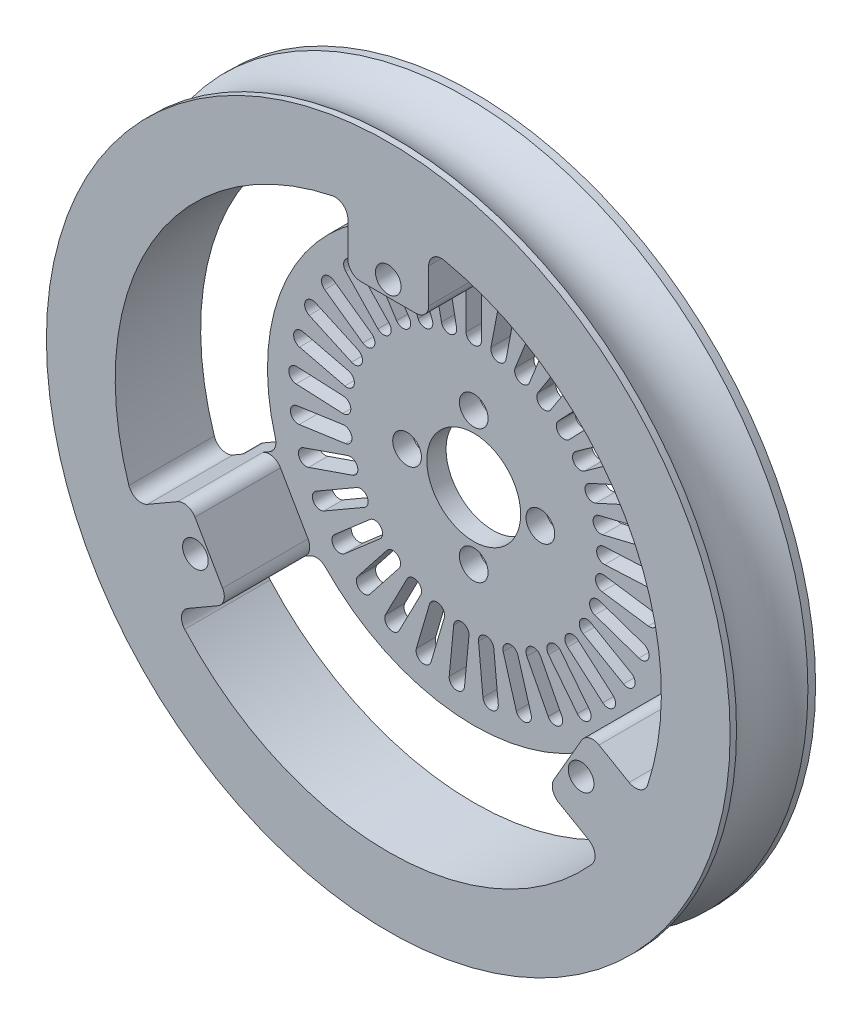
SolidWorks part; units mm, degrees
ref_plane "Plan de face" through (0, 0, 0) normal (0, 0, 1) x (1, 0, 0)
ref_plane "Plan de dessus" through (0, 0, 0) normal (0, 1, 0) x (1, 0, 0)
ref_plane "Plan de droite" through (0, 0, 0) normal (1, 0, 0) x (0, 0, -1)
sketch "Esquisse1" plane through (0, 0, 0) normal (0, 0, 1) x (1, 0, 0)
  circle A0 centre (0, 0) radius 33.8667
  dimension "D1" = 67.7333
extrude "Boss.-Extru.1" add sketch "Esquisse1" along normal blind 8.4667
sketch "Esquisse2" plane through (0, 0, 8.4667) normal (0, 0, 1) x (1, 0, 0)
  line L0 (4.0005, 25.2365) -> (4.0005, 21.8006)
  line L1 (2.7305, 20.5306) -> (-2.7305, 20.5306)
  line L2 (-4.0005, 21.8006) -> (-4.0005, 25.2365)
  line L3 (20.8801, -7.4357) -> (23.8557, -9.1537)
  line L4 (16.4147, -12.63) -> (19.1452, -7.9006)
  line L5 (19.8552, -16.0828) -> (16.8796, -14.3648)
  line L6 (-16.8796, -14.3648) -> (-19.8552, -16.0828)
  line L7 (-19.1452, -7.9006) -> (-16.4147, -12.63)
  line L8 (-23.8557, -9.1537) -> (-20.8801, -7.4357)
  arc A0 (-5.5301, 26.4797) -> (-25.6972, -8.4506) centre (0, 0) ccw
  arc A1 (4.0005, 21.8006) -> (2.7305, 20.5306) centre (2.7305, 21.8006) cw
  arc A2 (-2.7305, 20.5306) -> (-4.0005, 21.8006) centre (-2.7305, 21.8006) cw
  arc A3 (4.0005, 25.2365) -> (5.5301, 26.4797) centre (5.2705, 25.2365) cw
  arc A4 (-4.0005, 25.2365) -> (-5.5301, 26.4797) centre (-5.2705, 25.2365) ccw
  arc A5 (19.1452, -7.9006) -> (20.8801, -7.4357) centre (20.2451, -8.5356) cw
  arc A6 (16.8796, -14.3648) -> (16.4147, -12.63) centre (17.5146, -13.265) cw
  arc A7 (19.8552, -16.0828) -> (20.167, -18.0291) centre (19.2202, -17.1826) cw
  arc A8 (23.8557, -9.1537) -> (25.6972, -8.4506) centre (24.4907, -8.0539) ccw
  arc A9 (-16.4147, -12.63) -> (-16.8796, -14.3648) centre (-17.5146, -13.265) cw
  arc A10 (-20.8801, -7.4357) -> (-19.1452, -7.9006) centre (-20.2451, -8.5356) cw
  arc A11 (-23.8557, -9.1537) -> (-25.6972, -8.4506) centre (-24.4907, -8.0539) cw
  arc A12 (-19.8552, -16.0828) -> (-20.167, -18.0291) centre (-19.2202, -17.1826) ccw
  arc A13 (-20.167, -18.0291) -> (20.167, -18.0291) centre (0, 0) ccw
  arc A14 (25.6972, -8.4506) -> (5.5301, 26.4797) centre (0, 0) ccw
  point P5 (0, 20.5306)
  point P9 (4.0005, 20.5306)
  point P12 (-4.0005, 20.5306)
  point P15 (4.0005, 26.7536)
  point P45 (0, 0)
  dimension "D1" = 54.102
  dimension "D4" = 1.27
  dimension "D5" = 1.27
  dimension "D2" = 8.001
  dimension "D3" = 6.223
  dimension "D6" = 3
extrude "Enlèv. mat.-Extru.1" cut sketch "Esquisse2" against normal up to next
sketch "Esquisse7" plane through (0, 0, 0) normal (0, 1, 0) x (1, 0, 0)
  line L0 (0, -31.0899) -> (0, 31.0899) construction
  line L1 (-33.8667, 0) -> (-33.8667, -8.4667) construction
  line L2 (-33.8667, -0.762) -> (-33.8667, -7.8317)
  arc A0 (-33.8667, -7.8317) -> (-33.8667, -0.762) centre (-38.151, -4.2968) ccw
  point P0 (-32.5967, -4.2968)
  point P12 (0.6483, -31.0899)
  point P13 (0, 0)
  dimension "D1" = 0.635
  dimension "D2" = 1.27
  dimension "D3" = 0.762
revolve "Enlèvement de matière-Révolution4" cut sketch "Esquisse7" angle 360 about L0
sketch "Esquisse8" plane through (0, 0, 0) normal (0, 0, 1) x (1, 0, 0)
  line L0 (-22.7559, -8.5187) -> (-20.2341, -7.0628)
  line L1 (-18.7554, -15.4478) -> (-16.2336, -13.9919)
  line L2 (-16.4147, -12.63) -> (-19.1452, -7.9006) construction
  line L3 (-20.4902, -14.9829) -> (-23.2207, -10.2536)
  line L4 (4.0005, 23.9665) -> (4.0005, 21.0547)
  line L5 (-4.0005, 23.9665) -> (-4.0005, 21.0547)
  line L6 (-2.7305, 25.2365) -> (2.7305, 25.2365)
  line L7 (22.7559, -8.5187) -> (20.2341, -7.0628)
  line L8 (18.7554, -15.4478) -> (16.2336, -13.9919)
  line L9 (23.2207, -10.2536) -> (20.4902, -14.9829)
  line L10 (19.1452, -7.9006) -> (16.4147, -12.63) construction
  line L11 (-2.7305, 20.5306) -> (2.7305, 20.5306) construction
  arc A0 (-4.9621, 19.8227) -> (-19.648, -5.614) centre (0, 0) ccw
  arc A1 (-14.6859, -14.2086) -> (14.6859, -14.2086) centre (0, 0) ccw
  arc A2 (19.648, -5.614) -> (4.9621, 19.8227) centre (0, 0) ccw
  arc A3 (4.0005, 21.0547) -> (4.9621, 19.8227) centre (5.2705, 21.0547) ccw
  arc A4 (-4.0005, 21.0547) -> (-4.9621, 19.8227) centre (-5.2705, 21.0547) cw
  arc A5 (-20.2341, -7.0628) -> (-19.648, -5.614) centre (-20.8691, -5.9629) ccw
  arc A6 (-16.2336, -13.9919) -> (-14.6859, -14.2086) centre (-15.5986, -15.0917) cw
  arc A7 (16.2336, -13.9919) -> (14.6859, -14.2086) centre (15.5986, -15.0917) ccw
  arc A8 (20.2341, -7.0628) -> (19.648, -5.614) centre (20.8691, -5.9629) cw
  arc A9 (22.7559, -8.5187) -> (23.2207, -10.2536) centre (22.1209, -9.6186) cw
  arc A10 (18.7554, -15.4478) -> (20.4902, -14.9829) centre (19.3904, -14.3479) ccw
  arc A11 (-18.7554, -15.4478) -> (-20.4902, -14.9829) centre (-19.3904, -14.3479) cw
  arc A12 (-22.7559, -8.5187) -> (-23.2207, -10.2536) centre (-22.1209, -9.6186) ccw
  arc A13 (-4.0005, 23.9665) -> (-2.7305, 25.2365) centre (-2.7305, 23.9665) cw
  arc A14 (4.0005, 23.9665) -> (2.7305, 25.2365) centre (2.7305, 23.9665) ccw
  point P34 (-15.3539, -13.484)
  point P37 (15.3539, -13.484)
  point P40 (19.3544, -6.5549)
  point P43 (23.8557, -9.1537)
  point P46 (19.8552, -16.0828)
  point P49 (-19.8552, -16.0828)
  point P52 (-23.8557, -9.1537)
  point P55 (-4.0005, 25.2365)
  point P58 (4.0005, 25.2365)
  dimension "D1" = 20.4343
  dimension "D2" = 1.27
extrude "Boss.-Extru.2" add sketch "Esquisse8" against normal blind 1.905
sketch "Esquisse9" plane through (0, 0, -1.905) normal (0, 0, -1) x (-1, 0, 0)
  circle A0 centre (0, 0) radius 4.6482
  dimension "D1" = 9.2964
extrude "Enlèv. mat.-Extru.5" cut sketch "Esquisse9" against normal through all
sketch "Esquisse10" plane through (0, 0, 0) normal (0, 0, 1) x (1, 0, 0)
  circle A0 centre (0, 6.604) radius 1.4224
  circle A1 centre (6.604, 0) radius 1.4224
  circle A2 centre (0, -6.604) radius 1.4224
  circle A3 centre (-6.604, 0) radius 1.4224
  point P12 (0, 0)
  dimension "D1" = 2.8448
  dimension "D2" = 6.604
  dimension "D3" = 4
extrude "Enlèv. mat.-Extru.6" cut sketch "Esquisse10" against normal through all
sketch "Esquisse11" plane through (0, 0, -1.905) normal (0, 0, -1) x (-1, 0, 0)
  line L0 (-2.7305, 25.2365) -> (2.7305, 25.2365) construction
  circle A0 centre (0, 22.0615) radius 1.27
  circle A1 centre (19.1058, -11.0308) radius 1.27
  circle A2 centre (-19.1058, -11.0308) radius 1.27
  point P11 (0, 0)
  dimension "D1" = 2.54
  dimension "D2" = 3.175
  dimension "D3" = 3
extrude "Enlèv. mat.-Extru.7" cut sketch "Esquisse11" against normal through all
sketch "Esquisse12" plane through (0, 0, -1.905) normal (0, 0, -1) x (-1, 0, 0)
  line L0 (0, 17.5768) -> (0, 12.954) construction
  line L1 (0.762, 17.5768) -> (0.762, 12.954)
  line L2 (-0.762, 17.5768) -> (-0.762, 12.954)
  line L3 (3.3264, 17.2592) -> (2.4516, 12.7199) construction
  line L4 (4.0747, 17.115) -> (3.1998, 12.5757)
  line L5 (2.5782, 17.4034) -> (1.7033, 12.8641)
  line L6 (6.5326, 16.3177) -> (4.8145, 12.0261) construction
  line L7 (7.2401, 16.0345) -> (5.5219, 11.7429)
  line L8 (5.8252, 16.6009) -> (4.1071, 12.3093)
  line L9 (9.5027, 14.7865) -> (7.0035, 10.8976) construction
  line L10 (10.1438, 14.3746) -> (7.6445, 10.4856)
  line L11 (8.8617, 15.1985) -> (6.3624, 11.3096)
  line L12 (12.1294, 12.7209) -> (8.9393, 9.3753) construction
  line L13 (12.6809, 12.1951) -> (9.4908, 8.8494)
  line L14 (11.5779, 13.2468) -> (8.3878, 9.9011)
  line L15 (14.3176, 10.1955) -> (10.552, 7.5141) construction
  line L16 (14.7596, 9.5748) -> (10.994, 6.8934)
  line L17 (13.8756, 10.8163) -> (10.11, 8.1348)
  line L18 (15.9884, 7.3017) -> (11.7834, 5.3813) construction
  line L19 (16.305, 6.6085) -> (12.0999, 4.6881)
  line L20 (15.6719, 7.9948) -> (11.4668, 6.0744)
  line L21 (17.0813, 4.1439) -> (12.5888, 3.054) construction
  line L22 (17.261, 3.4034) -> (12.7685, 2.3135)
  line L23 (16.9017, 4.8844) -> (12.4092, 3.7945)
  line L24 (17.5569, 0.8363) -> (12.9393, 0.6164) construction
  line L25 (17.5931, 0.0752) -> (12.9756, -0.1448)
  line L26 (17.5206, 1.5975) -> (12.9031, 1.3775)
  line L27 (17.3979, -2.5014) -> (12.8221, -1.8435) construction
  line L28 (17.2894, -3.2557) -> (12.7137, -2.5978)
  line L29 (17.5063, -1.7472) -> (12.9306, -1.0893)
  line L30 (16.6101, -5.7488) -> (12.2415, -4.2368) construction
  line L31 (16.3609, -6.4689) -> (11.9923, -4.9569)
  line L32 (16.8593, -5.0287) -> (12.4908, -3.5167)
  line L33 (15.222, -8.7884) -> (11.2185, -6.477) construction
  line L34 (14.841, -9.4483) -> (10.8375, -7.1369)
  line L35 (15.603, -8.1285) -> (11.5995, -5.8171)
  line L36 (13.2837, -11.5104) -> (9.79, -8.4831) construction
  line L37 (12.7847, -12.0862) -> (9.291, -9.0589)
  line L38 (13.7827, -10.9345) -> (10.289, -7.9072)
  line L39 (10.8653, -13.8163) -> (8.0076, -10.1825) construction
  line L40 (10.2663, -14.2873) -> (7.4087, -10.6536)
  line L41 (11.4642, -13.3453) -> (8.6066, -9.7115)
  line L42 (8.0542, -15.6229) -> (5.9359, -11.514) construction
  line L43 (7.3769, -15.9721) -> (5.2586, -11.8631)
  line L44 (8.7314, -15.2737) -> (6.6132, -11.1648)
  line L45 (4.952, -16.8648) -> (3.6496, -12.4293) construction
  line L46 (4.2208, -17.0795) -> (2.9184, -12.644)
  line L47 (5.6831, -16.6501) -> (4.3807, -12.2146)
  line L48 (1.6708, -17.4972) -> (1.2314, -12.8953) construction
  line L49 (0.9122, -17.5696) -> (0.4728, -12.9678)
  line L50 (2.4293, -17.4248) -> (1.9899, -12.8229)
  line L51 (-1.6708, -17.4972) -> (-1.2314, -12.8953) construction
  line L52 (-2.4293, -17.4248) -> (-1.9899, -12.8229)
  line L53 (-0.9122, -17.5696) -> (-0.4728, -12.9678)
  line L54 (-4.952, -16.8648) -> (-3.6496, -12.4293) construction
  line L55 (-5.6831, -16.6501) -> (-4.3807, -12.2146)
  line L56 (-4.2208, -17.0795) -> (-2.9184, -12.644)
  line L57 (-8.0542, -15.6229) -> (-5.9359, -11.514) construction
  line L58 (-8.7314, -15.2737) -> (-6.6132, -11.1648)
  line L59 (-7.3769, -15.9721) -> (-5.2586, -11.8631)
  line L60 (-10.8653, -13.8163) -> (-8.0076, -10.1825) construction
  line L61 (-11.4642, -13.3453) -> (-8.6066, -9.7115)
  line L62 (-10.2663, -14.2873) -> (-7.4087, -10.6536)
  line L63 (-13.2837, -11.5104) -> (-9.79, -8.4831) construction
  line L64 (-13.7827, -10.9345) -> (-10.289, -7.9072)
  line L65 (-12.7847, -12.0862) -> (-9.291, -9.0589)
  line L66 (-15.222, -8.7884) -> (-11.2185, -6.477) construction
  line L67 (-15.603, -8.1285) -> (-11.5995, -5.8171)
  line L68 (-14.841, -9.4483) -> (-10.8375, -7.1369)
  line L69 (-16.6101, -5.7488) -> (-12.2415, -4.2368) construction
  line L70 (-16.8593, -5.0287) -> (-12.4908, -3.5167)
  line L71 (-16.3609, -6.4689) -> (-11.9923, -4.9569)
  line L72 (-17.3979, -2.5014) -> (-12.8221, -1.8435) construction
  line L73 (-17.5063, -1.7472) -> (-12.9306, -1.0893)
  line L74 (-17.2894, -3.2557) -> (-12.7137, -2.5978)
  line L75 (-17.5569, 0.8363) -> (-12.9393, 0.6164) construction
  line L76 (-17.5206, 1.5975) -> (-12.9031, 1.3775)
  line L77 (-17.5931, 0.0752) -> (-12.9756, -0.1448)
  line L78 (-17.0813, 4.1439) -> (-12.5888, 3.054) construction
  line L79 (-16.9017, 4.8844) -> (-12.4092, 3.7945)
  line L80 (-17.261, 3.4034) -> (-12.7685, 2.3135)
  line L81 (-15.9884, 7.3017) -> (-11.7834, 5.3813) construction
  line L82 (-15.6719, 7.9948) -> (-11.4668, 6.0744)
  line L83 (-16.305, 6.6085) -> (-12.0999, 4.6881)
  line L84 (-14.3176, 10.1955) -> (-10.552, 7.5141) construction
  line L85 (-13.8756, 10.8163) -> (-10.11, 8.1348)
  line L86 (-14.7596, 9.5748) -> (-10.994, 6.8934)
  line L87 (-12.1294, 12.7209) -> (-8.9393, 9.3753) construction
  line L88 (-11.5779, 13.2468) -> (-8.3878, 9.9011)
  line L89 (-12.6809, 12.1951) -> (-9.4908, 8.8494)
  line L90 (-9.5027, 14.7865) -> (-7.0035, 10.8976) construction
  line L91 (-8.8617, 15.1985) -> (-6.3624, 11.3096)
  line L92 (-10.1438, 14.3746) -> (-7.6445, 10.4856)
  line L93 (-6.5326, 16.3177) -> (-4.8145, 12.0261) construction
  line L94 (-5.8252, 16.6009) -> (-4.1071, 12.3093)
  line L95 (-7.2401, 16.0345) -> (-5.5219, 11.7429)
  line L96 (-3.3264, 17.2592) -> (-2.4516, 12.7199) construction
  line L97 (-2.5782, 17.4034) -> (-1.7033, 12.8641)
  line L98 (-4.0747, 17.115) -> (-3.1998, 12.5757)
  arc A0 (0.762, 17.5768) -> (-0.762, 17.5768) centre (0, 17.5768) ccw
  arc A1 (-0.762, 12.954) -> (0.762, 12.954) centre (0, 12.954) ccw
  arc A2 (4.0747, 17.115) -> (2.5782, 17.4034) centre (3.3264, 17.2592) ccw
  arc A3 (1.7033, 12.8641) -> (3.1998, 12.5757) centre (2.4516, 12.7199) ccw
  arc A4 (7.2401, 16.0345) -> (5.8252, 16.6009) centre (6.5326, 16.3177) ccw
  arc A5 (4.1071, 12.3093) -> (5.5219, 11.7429) centre (4.8145, 12.0261) ccw
  arc A6 (10.1438, 14.3746) -> (8.8617, 15.1985) centre (9.5027, 14.7865) ccw
  arc A7 (6.3624, 11.3096) -> (7.6445, 10.4856) centre (7.0035, 10.8976) ccw
  arc A8 (12.6809, 12.1951) -> (11.5779, 13.2468) centre (12.1294, 12.7209) ccw
  arc A9 (8.3878, 9.9011) -> (9.4908, 8.8494) centre (8.9393, 9.3753) ccw
  arc A10 (14.7596, 9.5748) -> (13.8756, 10.8163) centre (14.3176, 10.1955) ccw
  arc A11 (10.11, 8.1348) -> (10.994, 6.8934) centre (10.552, 7.5141) ccw
  arc A12 (16.305, 6.6085) -> (15.6719, 7.9948) centre (15.9884, 7.3017) ccw
  arc A13 (11.4668, 6.0744) -> (12.0999, 4.6881) centre (11.7834, 5.3813) ccw
  arc A14 (17.261, 3.4034) -> (16.9017, 4.8844) centre (17.0813, 4.1439) ccw
  arc A15 (12.4092, 3.7945) -> (12.7685, 2.3135) centre (12.5888, 3.054) ccw
  arc A16 (17.5931, 0.0752) -> (17.5206, 1.5975) centre (17.5569, 0.8363) ccw
  arc A17 (12.9031, 1.3775) -> (12.9756, -0.1448) centre (12.9393, 0.6164) ccw
  arc A18 (17.2894, -3.2557) -> (17.5063, -1.7472) centre (17.3979, -2.5014) ccw
  arc A19 (12.9306, -1.0893) -> (12.7137, -2.5978) centre (12.8221, -1.8435) ccw
  arc A20 (16.3609, -6.4689) -> (16.8593, -5.0287) centre (16.6101, -5.7488) ccw
  arc A21 (12.4908, -3.5167) -> (11.9923, -4.9569) centre (12.2415, -4.2368) ccw
  arc A22 (14.841, -9.4483) -> (15.603, -8.1285) centre (15.222, -8.7884) ccw
  arc A23 (11.5995, -5.8171) -> (10.8375, -7.1369) centre (11.2185, -6.477) ccw
  arc A24 (12.7847, -12.0862) -> (13.7827, -10.9345) centre (13.2837, -11.5104) ccw
  arc A25 (10.289, -7.9072) -> (9.291, -9.0589) centre (9.79, -8.4831) ccw
  arc A26 (10.2663, -14.2873) -> (11.4642, -13.3453) centre (10.8653, -13.8163) ccw
  arc A27 (8.6066, -9.7115) -> (7.4087, -10.6536) centre (8.0076, -10.1825) ccw
  arc A28 (7.3769, -15.9721) -> (8.7314, -15.2737) centre (8.0542, -15.6229) ccw
  arc A29 (6.6132, -11.1648) -> (5.2586, -11.8631) centre (5.9359, -11.514) ccw
  arc A30 (4.2208, -17.0795) -> (5.6831, -16.6501) centre (4.952, -16.8648) ccw
  arc A31 (4.3807, -12.2146) -> (2.9184, -12.644) centre (3.6496, -12.4293) ccw
  arc A32 (0.9122, -17.5696) -> (2.4293, -17.4248) centre (1.6708, -17.4972) ccw
  arc A33 (1.9899, -12.8229) -> (0.4728, -12.9678) centre (1.2314, -12.8953) ccw
  arc A34 (-2.4293, -17.4248) -> (-0.9122, -17.5696) centre (-1.6708, -17.4972) ccw
  arc A35 (-0.4728, -12.9678) -> (-1.9899, -12.8229) centre (-1.2314, -12.8953) ccw
  arc A36 (-5.6831, -16.6501) -> (-4.2208, -17.0795) centre (-4.952, -16.8648) ccw
  arc A37 (-2.9184, -12.644) -> (-4.3807, -12.2146) centre (-3.6496, -12.4293) ccw
  arc A38 (-8.7314, -15.2737) -> (-7.3769, -15.9721) centre (-8.0542, -15.6229) ccw
  arc A39 (-5.2586, -11.8631) -> (-6.6132, -11.1648) centre (-5.9359, -11.514) ccw
  arc A40 (-11.4642, -13.3453) -> (-10.2663, -14.2873) centre (-10.8653, -13.8163) ccw
  arc A41 (-7.4087, -10.6536) -> (-8.6066, -9.7115) centre (-8.0076, -10.1825) ccw
  arc A42 (-13.7827, -10.9345) -> (-12.7847, -12.0862) centre (-13.2837, -11.5104) ccw
  arc A43 (-9.291, -9.0589) -> (-10.289, -7.9072) centre (-9.79, -8.4831) ccw
  arc A44 (-15.603, -8.1285) -> (-14.841, -9.4483) centre (-15.222, -8.7884) ccw
  arc A45 (-10.8375, -7.1369) -> (-11.5995, -5.8171) centre (-11.2185, -6.477) ccw
  arc A46 (-16.8593, -5.0287) -> (-16.3609, -6.4689) centre (-16.6101, -5.7488) ccw
  arc A47 (-11.9923, -4.9569) -> (-12.4908, -3.5167) centre (-12.2415, -4.2368) ccw
  arc A48 (-17.5063, -1.7472) -> (-17.2894, -3.2557) centre (-17.3979, -2.5014) ccw
  arc A49 (-12.7137, -2.5978) -> (-12.9306, -1.0893) centre (-12.8221, -1.8435) ccw
  arc A50 (-17.5206, 1.5975) -> (-17.5931, 0.0752) centre (-17.5569, 0.8363) ccw
  arc A51 (-12.9756, -0.1448) -> (-12.9031, 1.3775) centre (-12.9393, 0.6164) ccw
  arc A52 (-16.9017, 4.8844) -> (-17.261, 3.4034) centre (-17.0813, 4.1439) ccw
  arc A53 (-12.7685, 2.3135) -> (-12.4092, 3.7945) centre (-12.5888, 3.054) ccw
  arc A54 (-15.6719, 7.9948) -> (-16.305, 6.6085) centre (-15.9884, 7.3017) ccw
  arc A55 (-12.0999, 4.6881) -> (-11.4668, 6.0744) centre (-11.7834, 5.3813) ccw
  arc A56 (-13.8756, 10.8163) -> (-14.7596, 9.5748) centre (-14.3176, 10.1955) ccw
  arc A57 (-10.994, 6.8934) -> (-10.11, 8.1348) centre (-10.552, 7.5141) ccw
  arc A58 (-11.5779, 13.2468) -> (-12.6809, 12.1951) centre (-12.1294, 12.7209) ccw
  arc A59 (-9.4908, 8.8494) -> (-8.3878, 9.9011) centre (-8.9393, 9.3753) ccw
  arc A60 (-8.8617, 15.1985) -> (-10.1438, 14.3746) centre (-9.5027, 14.7865) ccw
  arc A61 (-7.6445, 10.4856) -> (-6.3624, 11.3096) centre (-7.0035, 10.8976) ccw
  arc A62 (-5.8252, 16.6009) -> (-7.2401, 16.0345) centre (-6.5326, 16.3177) ccw
  arc A63 (-5.5219, 11.7429) -> (-4.1071, 12.3093) centre (-4.8145, 12.0261) ccw
  arc A64 (-2.5782, 17.4034) -> (-4.0747, 17.115) centre (-3.3264, 17.2592) ccw
  arc A65 (-3.1998, 12.5757) -> (-1.7033, 12.8641) centre (-2.4516, 12.7199) ccw
  point P3 (0, 15.2654)
  point P8 (0, 18.3388)
  point P9 (0, 12.192)
  point P10 (-0.762, 15.2654)
  point P16 (2.889, 14.9895)
  point P23 (5.6736, 14.1719)
  point P30 (8.2531, 12.8421)
  point P37 (10.5343, 11.0481)
  point P44 (12.4348, 8.8548)
  point P51 (13.8859, 6.3415)
  point P58 (14.8351, 3.599)
  point P65 (15.2481, 0.7264)
  point P72 (15.11, -2.1725)
  point P79 (14.4258, -4.9928)
  point P86 (13.2202, -7.6327)
  point P93 (11.5368, -9.9967)
  point P100 (9.4364, -11.9994)
  point P107 (6.995, -13.5684)
  point P114 (4.3008, -14.647)
  point P121 (1.4511, -15.1963)
  point P128 (-1.4511, -15.1963)
  point P135 (-4.3008, -14.647)
  point P142 (-6.995, -13.5684)
  point P149 (-9.4364, -11.9994)
  point P156 (-11.5368, -9.9967)
  point P163 (-13.2202, -7.6327)
  point P170 (-14.4258, -4.9928)
  point P177 (-15.11, -2.1725)
  point P184 (-15.2481, 0.7264)
  point P191 (-14.8351, 3.599)
  point P198 (-13.8859, 6.3415)
  point P205 (-12.4348, 8.8548)
  point P212 (-10.5343, 11.0481)
  point P219 (-8.2531, 12.8421)
  point P226 (-5.6736, 14.1719)
  point P233 (-2.889, 14.9895)
  point P238 (0, 0)
  dimension "D1" = 6.1468
  dimension "D2" = 1.524
  dimension "D3" = 12.192
  dimension "D4" = 33
extrude "Enlèv. mat.-Extru.8" cut sketch "Esquisse12" against normal through all
